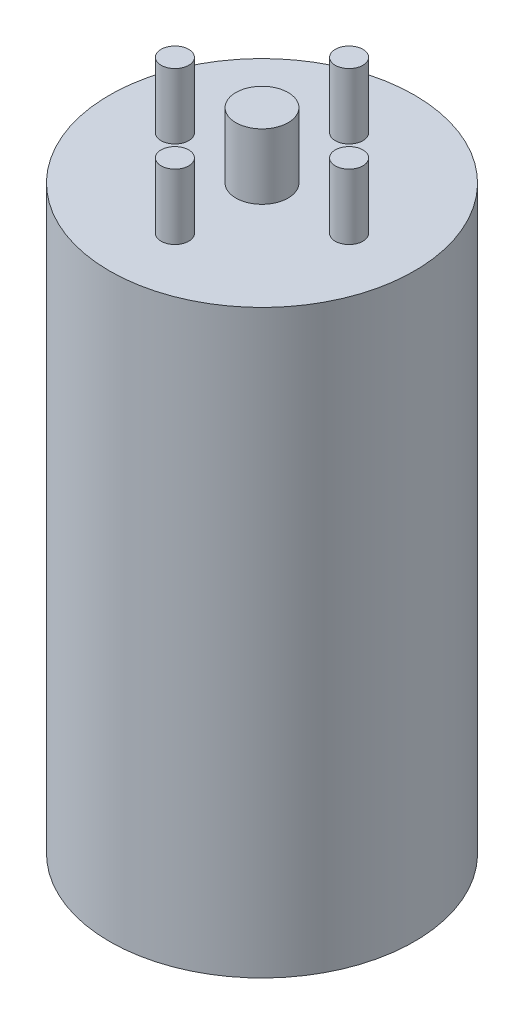
SolidWorks part; units mm, degrees
ref_plane "Front Plane" through (0, 0, 0) normal (0, 0, 1) x (1, 0, 0)
ref_plane "Top Plane" through (0, 0, 0) normal (0, 1, 0) x (1, 0, 0)
ref_plane "Right Plane" through (0, 0, 0) normal (1, 0, 0) x (0, 0, -1)
sketch "Sketch1" plane through (0, 0, 0) normal (0, 1, 0) x (1, 0, 0)
  circle A0 centre (0, 0) radius 14
  dimension "D1" = 28
extrude "Boss-Extrude1" add sketch "Sketch1" along normal blind 53.34
sketch "Sketch2" plane through (0, 53.34, 0) normal (0, 1, 0) x (1, 0, 0)
  line L0 (0, 14) -> (0, -14) construction
  line L1 (-14, 0) -> (14, 0) construction
  circle A0 centre (0, 0) radius 2.4
  circle A1 centre (0, 0) radius 14 construction
  circle A2 centre (8, 0) radius 1.27
  circle A3 centre (0, -8) radius 1.27
  circle A4 centre (-8, 0) radius 1.27
  circle A5 centre (0, 8) radius 1.27
  point P21 (0, 0)
  dimension "D1" = 4.8
  dimension "D3" = 2.54
  dimension "D2" = 8
  dimension "D4" = 4
extrude "Boss-Extrude2" add sketch "Sketch2" along normal blind 6
